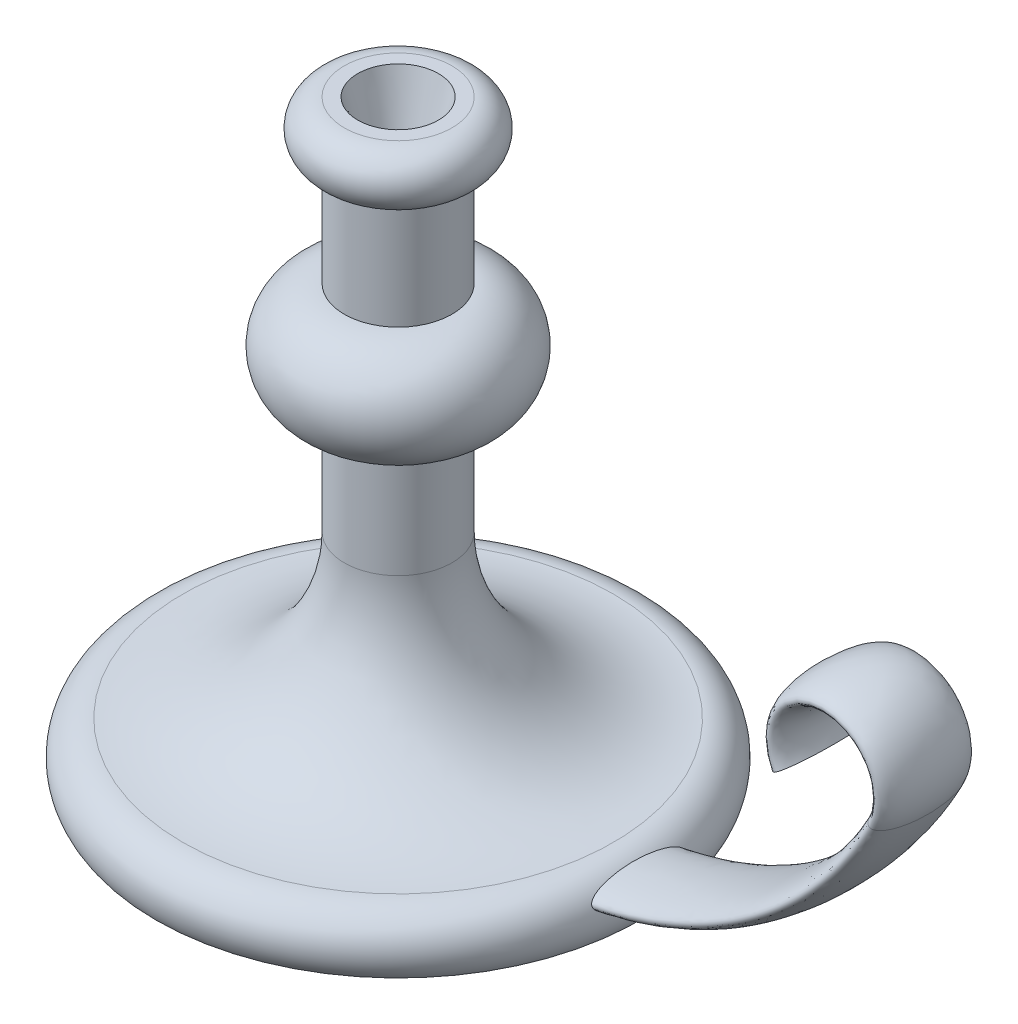
SolidWorks part; units mm, degrees
ref_plane "Płaszczyzna przednia" through (0, 0, 0) normal (0, 0, 1) x (1, 0, 0)
ref_plane "Płaszczyzna górna" through (0, 0, 0) normal (0, 1, 0) x (1, 0, 0)
ref_plane "Płaszczyzna prawa" through (0, 0, 0) normal (1, 0, 0) x (0, 0, -1)
sketch "Szkic1" plane through (0, 0, 0) normal (0, 0, 1) x (1, 0, 0)
  line L0 (0, 0) -> (0, 220)
  line L1 (0, 220) -> (20, 220)
  line L2 (20, 200) -> (20, 160)
  line L3 (20, 120) -> (20, 80)
  line L4 (90, 0) -> (0, 0)
  arc A0 (20, 220) -> (20, 200) centre (20, 210) cw
  arc A1 (20, 160) -> (20, 120) centre (20, 140) cw
  arc A2 (20, 80) -> (80, 20) centre (80, 80) ccw
  arc A4 (80, 20) -> (90, 0) centre (80, 7.5) cw
  dimension "D3" = 10
  dimension "D5" = 20
  dimension "D7" = 60
  dimension "D8" = 12.5
  dimension "D1" = 220
  dimension "D2" = 20
  dimension "D4" = 40
  dimension "D6" = 40
  dimension "D9" = 90
  dimension "D10" = 80
revolve "Obrót1" add sketch "Szkic1" angle 360 about L0
sketch "Szkic2" plane through (0, 0, 0) normal (0, 0, 1) x (1, 0, 0)
  line L0 (0, 10) -> (60, 10)
  line L1 (0, 126.8188) -> (0, -13.6376) construction
  line L2 (0, 200) -> (0, 160) construction
  arc A0 (60, 10) -> (192.6628, 89.9959) centre (60, 160) ccw
  arc A1 (192.6628, 89.9959) -> (157.2861, 89.9959) centre (174.9744, 99.3297) ccw
  point P10 (0, 0)
  dimension "D2" = 150
  dimension "D3" = 20
  dimension "D1" = 60
  dimension "D4" = 10
sketch "Szkic3" plane through (0, 0, 0) normal (1, 0, 0) x (0, 0, -1)
  ellipse E0 centre (0, 10) end of major axis (-17.5, 10) minor radius 5
  dimension "D1" = 10
  dimension "D2" = 35
sweep "Wyciągnięcie po ścieżce1" add profiles "Szkic3" path "Szkic2"
sketch "Szkic4" plane through (0, 220, 0) normal (0, 1, 0) x (1, 0, 0)
  circle A0 centre (0, 0) radius 15
  dimension "D1" = 30
extrude "Wytnij-wyciągnięcie3" cut sketch "Szkic4" against normal blind 25 draft 15 contours A0
